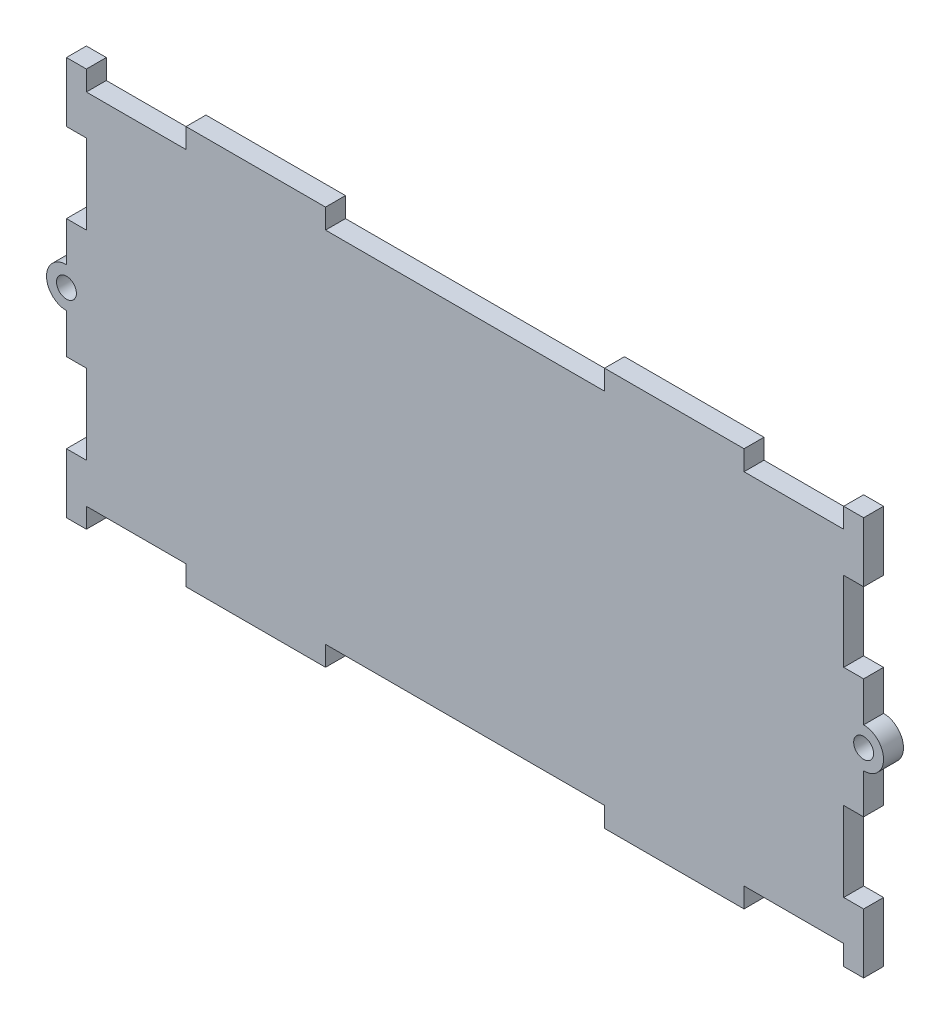
SolidWorks part; units mm, degrees
ref_plane "Plan de face" through (0, 0, 0) normal (0, 0, 1) x (1, 0, 0)
ref_plane "Plan de dessus" through (0, 0, 0) normal (0, 1, 0) x (1, 0, 0)
ref_plane "Plan de droite" through (0, 0, 0) normal (1, 0, 0) x (0, 0, -1)
sketch "Esquisse1" plane through (0, 0, 0) normal (0, 0, 1) x (1, 0, 0)
  line L0 (-35, 37.471) -> (35, 37.471)
  line L1 (35, 37.471) -> (35, 42.471)
  line L2 (35, 42.471) -> (70, 42.471)
  line L3 (70, 42.471) -> (70, 37.471)
  line L4 (70, 37.471) -> (95, 37.471)
  line L5 (100, 37.471) -> (100, 27.471)
  line L6 (100, 27.471) -> (95, 27.471)
  line L7 (95, 27.471) -> (95, 7.471)
  line L8 (95, 7.471) -> (100, 7.471)
  line L9 (100, 7.471) -> (100, -2.529)
  line L10 (107.529, -7.529) -> (0, -7.529) construction
  line L11 (0, -7.529) -> (0, 49.4765) construction
  line L12 (-100, 7.471) -> (-100, -2.529)
  line L13 (-95, 7.471) -> (-100, 7.471)
  line L14 (-95, 27.471) -> (-95, 7.471)
  line L15 (-100, 27.471) -> (-95, 27.471)
  line L16 (-100, 37.471) -> (-100, 27.471)
  line L17 (-70, 37.471) -> (-95, 37.471)
  line L18 (-70, 42.471) -> (-70, 37.471)
  line L19 (-35, 42.471) -> (-70, 42.471)
  line L20 (-35, 37.471) -> (-35, 42.471)
  line L21 (-35, -52.529) -> (-35, -57.529)
  line L22 (-35, -57.529) -> (-70, -57.529)
  line L23 (-70, -57.529) -> (-70, -52.529)
  line L24 (-70, -52.529) -> (-95, -52.529)
  line L25 (-100, -52.529) -> (-100, -42.529)
  line L26 (-100, -42.529) -> (-95, -42.529)
  line L27 (-95, -42.529) -> (-95, -22.529)
  line L28 (-95, -22.529) -> (-100, -22.529)
  line L29 (-100, -22.529) -> (-100, -12.529)
  line L30 (100, -22.529) -> (100, -12.529)
  line L31 (95, -22.529) -> (100, -22.529)
  line L32 (95, -42.529) -> (95, -22.529)
  line L33 (100, -42.529) -> (95, -42.529)
  line L34 (100, -52.529) -> (100, -42.529)
  line L35 (70, -52.529) -> (95, -52.529)
  line L36 (70, -57.529) -> (70, -52.529)
  line L37 (35, -57.529) -> (70, -57.529)
  line L38 (35, -52.529) -> (35, -57.529)
  line L39 (-35, -52.529) -> (35, -52.529)
  line L40 (100, -2.529) -> (100, -12.529) construction
  line L41 (100, -52.529) -> (100, -57.5272)
  line L42 (100, -57.5272) -> (95, -57.5272)
  line L43 (95, -57.5272) -> (95, -52.529)
  line L44 (95, -42.5272) -> (95, -57.5272) construction
  line L45 (-100, -52.529) -> (-100, -57.529)
  line L46 (-100, -57.529) -> (-95, -57.529)
  line L47 (-95, -57.529) -> (-95, -52.529)
  line L48 (-100, 37.471) -> (-100, 42.471)
  line L49 (-100, 42.471) -> (-95, 42.471)
  line L50 (-95, 42.471) -> (-95, 37.471)
  line L51 (100, 37.471) -> (100, 42.4728)
  line L52 (100, 42.4728) -> (95, 42.4728)
  line L53 (95, 42.4728) -> (95, 37.471)
  arc A0 (100, -2.529) -> (100, -12.529) centre (100, -7.529) cw
  circle A1 centre (100, -7.529) radius 2.4983
  circle A2 centre (-100, -7.529) radius 2.4983
  arc A3 (-100, -2.529) -> (-100, -12.529) centre (-100, -7.529) ccw
  point P24 (0, 37.471)
  point P46 (0, -52.529)
  dimension "D11" = 4.9966
  dimension "D1" = 100
  dimension "d2" = 40
  dimension "d3" = 5
  dimension "D4" = 45
  dimension "D5" = 5
  dimension "D6" = 5
  dimension "D7" = 35
  dimension "D8" = 70
  dimension "D9" = 20
  dimension "D10" = 10
extrude "Boss.-Extru.1" add sketch "Esquisse1" along normal blind 5
